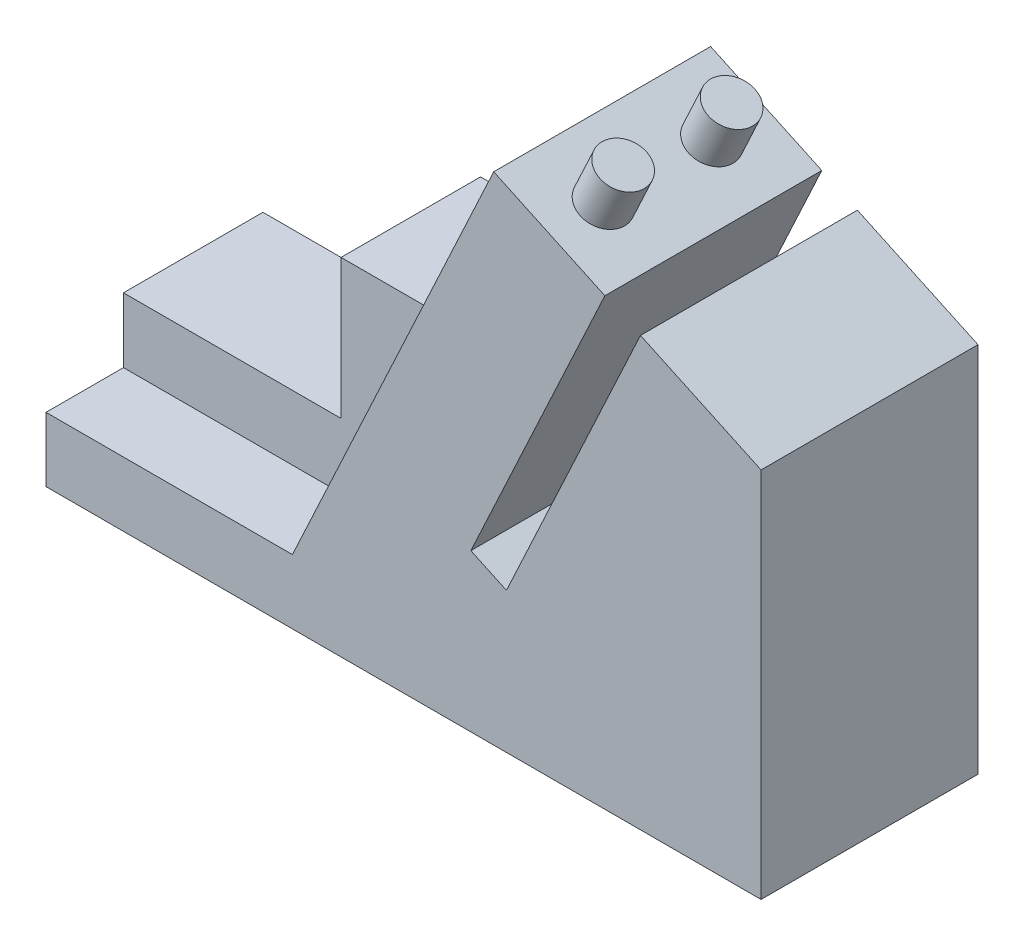
SolidWorks part; units mm, degrees
material "Ductile Iron"
ref_plane "Front Plane" through (0, 0, 0) normal (0, 0, 1) x (1, 0, 0)
ref_plane "Top Plane" through (0, 0, 0) normal (0, 1, 0) x (1, 0, 0)
ref_plane "Right Plane" through (0, 0, 0) normal (1, 0, 0) x (0, 0, -1)
sketch "Sketch1" plane through (0, 0, 0) normal (0, 0, 1) x (1, 0, 0)
  line L0 (60289.5757, -8339.2597) -> (-32008.7953, -8339.2597)
  line L1 (-32008.7953, -8339.2597) -> (-32008.7953, -32.9601)
  line L2 (-32008.7953, -32.9601) -> (-203.5178, -32.9601)
  line L3 (-203.5178, -32.9601) -> (25778.6942, 55752.3773)
  line L4 (44721.8591, 46929.5334) -> (60289.5757, 39678.8161)
  line L5 (60289.5757, 39678.8161) -> (60289.5757, -8339.2597)
  line L6 (-32008.7953, -32.9601) -> (-32008.7953, 9785.8673)
  line L7 (-32008.7953, 9785.8673) -> (-3052.0811, 9785.8673)
  line L8 (-3052.0811, 9785.8673) -> (-3052.0811, 27785.8673)
  line L9 (-3052.0811, 27785.8673) -> (12753.1963, 27785.8673)
  line L10 (25778.6942, 55752.3773) -> (40128.4142, 49068.9461)
  line L11 (40128.4142, 49068.9461) -> (22828.6246, 11925.28)
  line L12 (22828.6246, 11925.28) -> (27422.0695, 9785.8673)
  line L13 (27422.0695, 9785.8673) -> (44721.8591, 46929.5334)
  point P2 (60289.5757, -8339.2597)
  point P15 (27227.3443, 57724.4277)
  point P16 (25778.6942, 55752.3773)
  point P17 (27422.0695, 9785.8673)
extrude "Boss-Extrude3" add sketch "Sketch1" along normal blind 28000 contours L2 L3 L10 L11 L12 L13 L4 L5 L0 L1
sketch "Sketch4" plane through (0, 0, 0) normal (0, 0, 1) x (1, 0, 0)
  line L0 (-32008.7953, -32.9601) -> (-32008.7953, 8328.7122)
  line L1 (-32008.7953, 8328.7122) -> (-3925.4786, 8328.7122)
  line L2 (-3925.4786, 8328.7122) -> (-3925.4786, 26328.7122)
  line L3 (-3925.4786, 26328.7122) -> (12074.5214, 26328.7122)
  line L4 (-203.5178, -32.9601) -> (25778.6942, 55752.3773) construction
  line L5 (-32008.7953, -32.9601) -> (-203.5178, -32.9601)
  line L6 (-203.5178, -32.9601) -> (12074.5214, 26328.7122)
extrude "Boss-Extrude4" add sketch "Sketch4" along normal blind 18000
sketch "Sketch6" plane through (25933.3186, 55680.3605, 0) normal (0.4222, 0.9065, 0) x (0.9065, -0.4222, 0)
  line L0 (7744.3294, -28000) -> (7744.3294, -21000)
  line L1 (-170.573, -28000) -> (15659.2318, -28000) construction
  line L2 (7744.3294, 0) -> (7744.3294, -7000)
  line L3 (-170.573, 0) -> (15659.2318, 0) construction
sketch "Sketch7" plane through (25933.3186, 55680.3605, 0) normal (0.4222, 0.9065, 0) x (0.9065, -0.4222, 0)
  circle A0 centre (7744.3294, -21000) radius 3000
  circle A1 centre (7744.3294, -7000) radius 3000
extrude "Boss-Extrude6" add sketch "Sketch7" along normal blind 6000 contours A0 | A1
